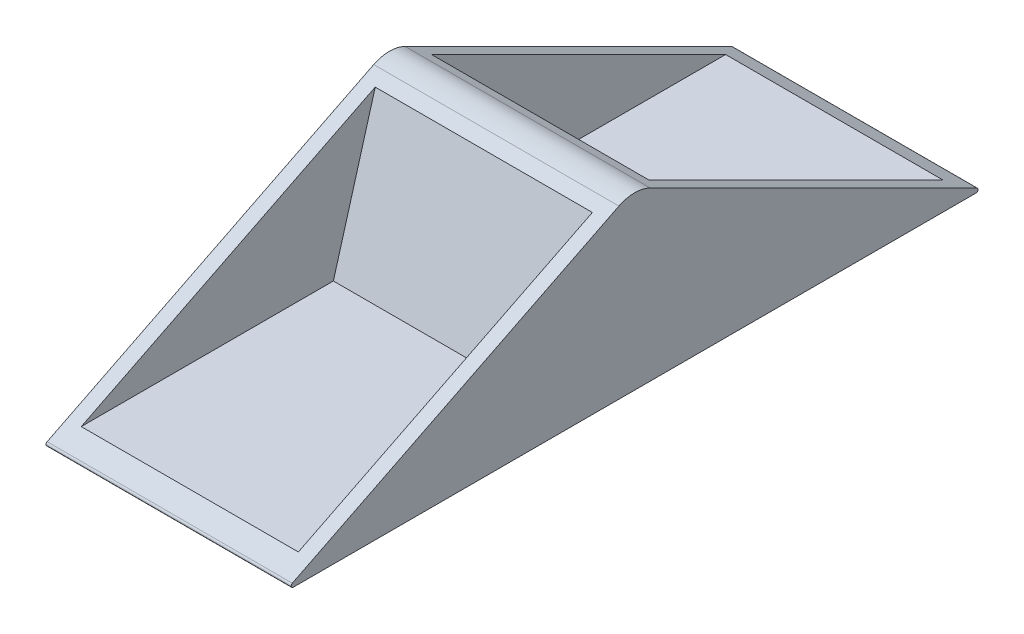
SolidWorks part; units mm, degrees
ref_plane "Front Plane" through (0, 0, 0) normal (0, 0, 1) x (1, 0, 0)
ref_plane "Top Plane" through (0, 0, 0) normal (0, 1, 0) x (1, 0, 0)
ref_plane "Right Plane" through (0, 0, 0) normal (1, 0, 0) x (0, 0, -1)
sketch "Sketch2" plane through (0, 0, 0) normal (1, 0, 0) x (0, 0, -1)
  line L3 (0, 0) -> (50, 0)
  line L4 (0, 0) -> (0, 25)
  line L5 (0, 25) -> (50, 0)
extrude "Boss-Extrude5" add sketch "Sketch2" along normal blind 35
mirror "Mirror1" of "Boss-Extrude5"
shell "Shell8" thickness 2
sketch3d "3DSketch9"
  line L0 (33, 25, 0) -> (33, 22.9875, -4.0249)
  line L1 (33, 2, -46) -> (33, 25, 0) construction
  line L2 (33, 22.9875, -4.0249) -> (33, 2, -4.0249)
  line L3 (33, 2, 46) -> (33, 2, -46) construction
  line L4 (33, 25, 0) -> (33, 22.9875, 4.0249)
  line L5 (33, 2, 46) -> (33, 25, 0) construction
  line L6 (33, 22.9875, 4.0249) -> (33, 2, 4.0249)
  line L7 (33, 2, 4.0249) -> (33, 2, -4.0249)
extrude "Boss-Extrude6" add sketch "3DSketch9" along a picked direction on the side of the normal blind 31
sketch3d "3DSketch10"
  line L0 (33, 2, -4.0249) -> (33, 2, -10)
  line L1 (33, 2, -4.0249) -> (33, 2, -46) construction
  line L2 (33, 2, -10) -> (33, 22.9875, -4.0249)
  line L3 (33, 22.9875, -4.0249) -> (33, 2, -4.0249)
  line L4 (33, 2, 4.0249) -> (33, 2, 10)
  line L5 (33, 2, 46) -> (33, 2, 4.0249) construction
  line L6 (33, 2, 10) -> (33, 22.9875, 4.0249)
  line L7 (33, 22.9875, 4.0249) -> (33, 2, 4.0249)
extrude "Boss-Extrude7" add sketch "3DSketch10" along a picked direction on the side against the normal blind 31
fillet "Fillet1" radius 5 1 edges
fillet "Fillet2" radius 0.3 1 edges at (17.5, 0, -50)
fillet "Fillet3" radius 0.3 1 edges at (17.5, 0, 50)
sketch "Sketch3" plane through (0, 0, 0) normal (0, -1, 0) x (1, 0, 0)
  line L0 (17.5, -48.7292) -> (17.5, 48.7292)
  line L1 (0, -48.7292) -> (35, -48.7292) construction
  line L2 (35, 48.7292) -> (0, 48.7292) construction
  line L4 (28.5, -11) -> (6.5, -11)
  line L5 (28.5, -11) -> (28.5, 11)
  line L6 (28.5, 11) -> (6.5, 11)
  line L7 (6.5, -11) -> (6.5, 11)
  line L8 (28.5, -11) -> (6.5, 11) construction
  line L9 (28.5, 11) -> (6.5, -11) construction
  point P6 (17.5, 0)
extrude "Cut-Extrude2" cut sketch "Sketch3" against normal blind 1 contours L7 L4 L0 L6 | L5 L6 L0 L4
sketch "Schizzo2" plane through (0, 0, 0) normal (-1, 0, 0) x (0, 0, 1)
  line L0 (-2.2361, 23.882) -> (-2.2361, 0)
  line L1 (48.7292, 0) -> (-48.7292, 0) construction
  line L2 (2.2361, 23.882) -> (2.2361, 0)
